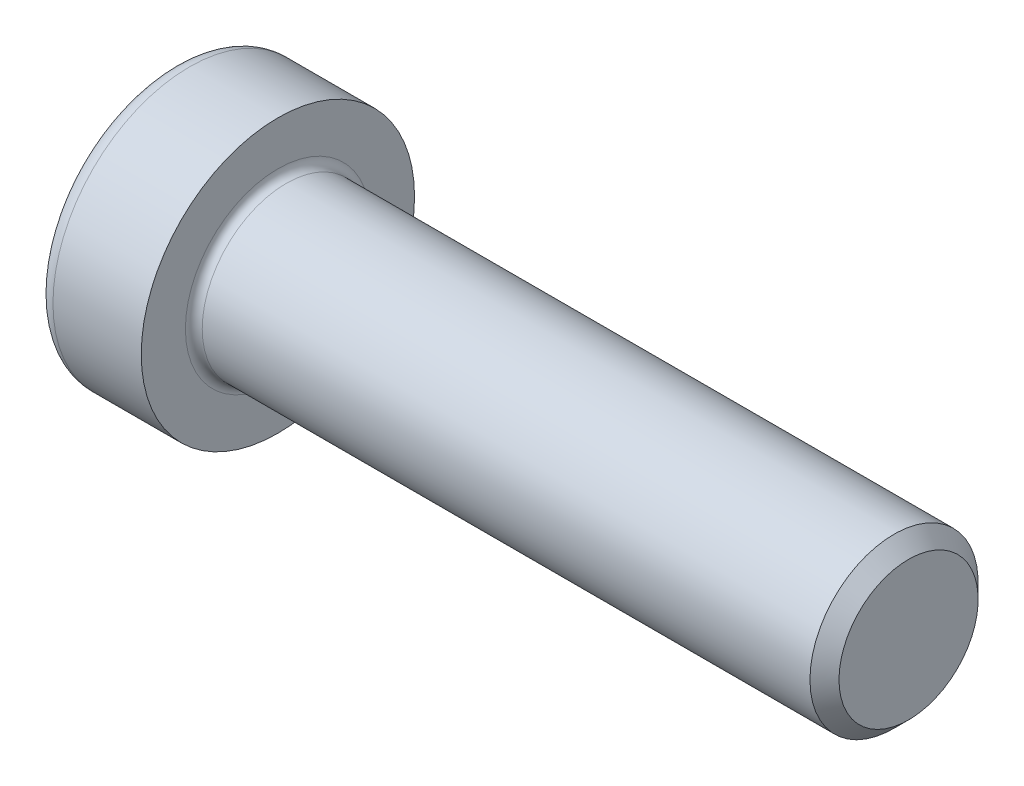
SolidWorks part; units mm, degrees
revolve "Base-Revolve" add sketch "BodySke"
sketch "BodySke" plane through (0, 0, 0) normal (0, 0, 1) x (1, 0, 0)
  line L0 (0, 0) -> (0, 6.5)
  line L1 (0, 6.5) -> (5, 6.5)
  line L2 (5, 6.5) -> (5, 4)
  line L3 (5, 4) -> (34.3095, 4)
  line L4 (35, 3.3095) -> (35, 0)
  line L5 (35, 0) -> (0, 0)
  line L6 (-31.75, 0) -> (127, 0) construction
  line L8 (35, 3.3095) -> (34.3095, 4)
  line L10 (35, -3.3095) -> (34.3095, -4) construction
  line L11 (6.25, 4.525) -> (6.25, -1.825) construction
  line L12 (8.75, 4.525) -> (8.75, -1.825) construction
  line L13 (-25, 4.525) -> (-25, -1.825) construction
  dimension "Head_ht" = 5
  dimension "Length" = 30
  dimension "Body_ch_ang" = 45
  dimension "Diameter" = 8
  dimension "Minor_dia" = 6.619
  dimension "Advance" = 1.25
  dimension "Thread_nom" = 26.25
  dimension "Thread_length" = 60
  dimension "Head_dia" = 13
cosmetic thread "ThreadCosmetic" [suppressed]
fillet "Fillet1" radius 0.4 1 edges at (5, 0, 4)
fillet "Fillet2" radius 0.8 1 edges at (0, 0, 6.5)
ref_plane "Plane1" through (0, 0, 0) normal (0, 0, 1) x (1, 0, 0)
ref_plane "Plane2" through (0, 0, 0) normal (0, 1, 0) x (1, 0, 0)
ref_plane "Plane3" through (0, 0, 0) normal (1, 0, 0) x (0, 0, -1)
sketch "Sketch2" plane through (0, 0, 0) normal (0, 0, 1) x (1, 0, 0)
  line L0 (0, 2.5) -> (3.8, 2.5)
  line L1 (3.8, 2.5) -> (5.2434, 0)
  line L2 (-31.75, 0) -> (127, 0) construction
  line L3 (5.2434, 0) -> (0, 0)
  line L4 (0, 0) -> (0, 2.5)
  line L6 (0, 0) -> (47.625, 0) construction
  dimension "D1" = 2.5
  dimension "D2" = 60
  dimension "Depth" = 3.8
revolve "Hex-PreBroach" cut sketch "Sketch2" angle 360 about L6
sketch "Sketch3" plane through (0, 0, 0) normal (-1, 0, 0) x (0, 0.5, 0.866)
  line L0 (1.4434, 2.5) -> (-1.4434, 2.5)
  line L1 (-1.4434, 2.5) -> (-2.8868, 0)
  line L2 (1.4434, 2.5) -> (2.8868, 0)
  line L3 (1.4434, -2.5) -> (2.8868, 0)
  line L4 (1.4434, -2.5) -> (-1.4434, -2.5)
  line L5 (-1.4434, -2.5) -> (-2.8868, 0)
  dimension "D1" = 2.5
  dimension "D2" = 2.5
  dimension "Hex_size" = 5
extrude "Hex" cut sketch "Sketch3" against normal blind 3.8
sketch "ThdSchSke" plane through (0, 0, 0) normal (0, 0, 1) x (1, 0, 0)
  line L0 (8.75, -3.3095) -> (8.2665, -4)
  line L1 (8.75, -3.3095) -> (9.2335, -4)
  line L2 (9.2335, -4) -> (9.2335, -5)
  line L3 (-3.175, 0) -> (5.1513, 0) construction
  line L4 (0, 5.7) -> (0, -5.7) construction
  line L5 (9.2335, -5) -> (8.2665, -5)
  line L6 (8.2665, -5) -> (8.2665, -4)
  dimension "Thread_minor" = 6.619
  dimension "Diameter" = 8
  dimension "Start" = 8.75
revolve "ThreadSchematic" [suppressed] cut sketch "ThdSchSke" angle 360 about L3
pattern_linear "ThdSchPat" [suppressed]
equation "\"D2@Sketch3\" = \"Hex_size@Sketch3\" / 2"
equation "\"D1@Sketch3\" = \"Hex_size@Sketch3\" / 2"
equation "\"D1@Sketch2\" = \"Hex_size@Sketch3\" / 2"
equation "\"Thread_minor@ThreadCosmetic\"  =  \"Minor_dia@BodySke\""
equation "\"Depth@Sketch2\" =  \"Key_eng@Hex\""
equation "\"Thread_length@ThreadCosmetic\" = ((sgn( (\"Length@BodySke\" - \"Advance@BodySke\" * 3.0) - \"Thread_nom@BodySke\" )-1)*( (\"Length@BodySke\" - \"Advance@BodySke\" * 3.0) - \"Thread_nom@BodySke\" ))/-2+ \"Thread_nom@BodySke\""
equation "\"Thread_minor@ThdSchSke\" = \"Minor_dia@BodySke\""
equation "\"Diameter@ThdSchSke\" = \"Diameter@BodySke\""
equation "\"Overcut@ThdSchSke\" = \"Diameter@BodySke\" * 1.25"
equation "\"Start@ThdSchSke\" = \"Head_ht@BodySke\" + \"Length@BodySke\" - \"Thread_length@ThreadCosmetic\"  '---Non-countersunk---"
equation "\"Num_threads@ThdSchPat\" = int( \"Thread_length@ThreadCosmetic\" / \"Advance@BodySke\" + 0.999 )  + 1"
equation "\"Advance@ThdSchPat\" = \"Thread_length@ThreadCosmetic\" /  (\"Num_threads@ThdSchPat\" - 1) 'relax it"
equation "\"Num_threads@ThdSchPat\" = \"Num_threads@ThdSchPat\" - sgn( \"Num_threads@ThdSchPat\" - 1) '---chamfered tips only---"
